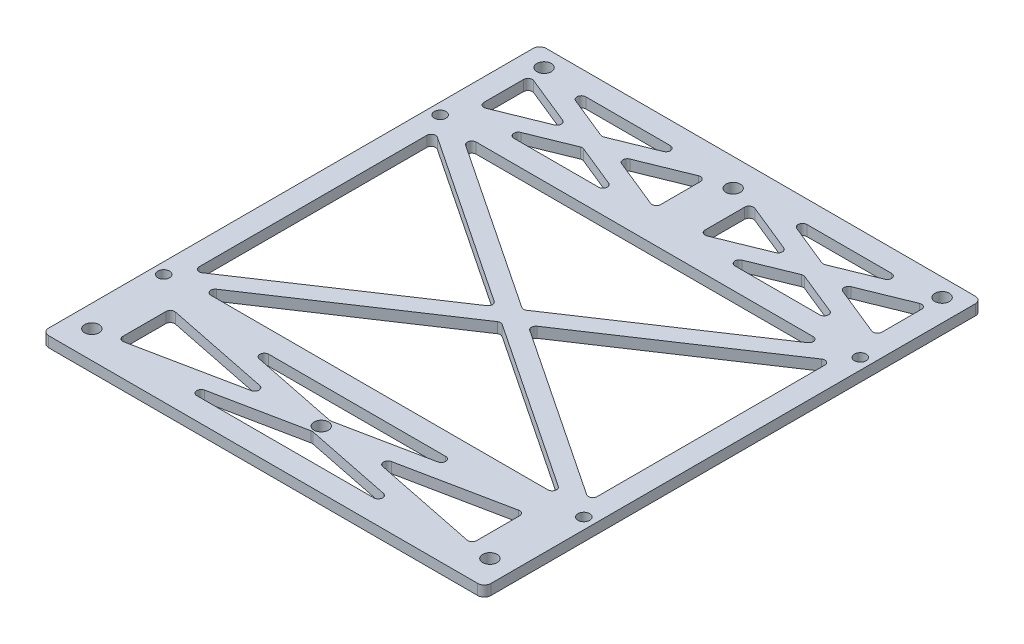
SolidWorks part; units mm, degrees
ref_plane "Front Plane" through (0, 0, 0) normal (0, 0, 1) x (1, 0, 0)
ref_plane "Top Plane" through (0, 0, 0) normal (0, 1, 0) x (1, 0, 0)
ref_plane "Right Plane" through (0, 0, 0) normal (1, 0, 0) x (0, 0, -1)
sketch "Sketch2" plane through (0, 0, 0) normal (0, 1, 0) x (1, 0, 0)
  line L0 (-90, -100) -> (90, -100) construction
  line L1 (-100, -112.5) -> (100, -112.5)
  line L2 (-100, -112.5) -> (-100, 112.5)
  line L3 (-100, 112.5) -> (100, 112.5)
  line L4 (100, -112.5) -> (100, 112.5)
  line L5 (-100, -112.5) -> (100, 112.5) construction
  line L6 (-100, 112.5) -> (100, -112.5) construction
  line L7 (-90, 100) -> (90, 100) construction
  line L8 (-95, -62.5) -> (95, -62.5) construction
  line L9 (-95, -62.5) -> (-95, 62.5) construction
  line L10 (-95, 62.5) -> (95, 62.5) construction
  line L11 (95, -62.5) -> (95, 62.5) construction
  line L12 (-95, -62.5) -> (95, 62.5) construction
  line L13 (-95, 62.5) -> (95, -62.5) construction
  circle A0 centre (-90, -100) radius 76.2 construction
  circle A1 centre (90, -100) radius 76.2 construction
  circle A2 centre (0, 100) radius 76.2 construction
  point P0 (0, 0)
  point P15 (0, 0)
  point P16 (0, -100)
  point P21 (0, 100)
  dimension "D3" = 152.4
  dimension "D1" = 200
  dimension "D2" = 225
  dimension "D4" = 100
  dimension "D5" = 180
  dimension "D6" = 100
  dimension "D7" = 190
  dimension "D8" = 125
extrude "Boss-Extrude1" add sketch "Sketch2" along normal blind 4.7625
hole_wizard "M5 Clearance Hole1" positions "Sketch5" profile "Sketch6" hole size "M5" standard "ANSI Metric" end condition through all
sketch "Sketch5" plane through (0, 4.7625, 0) normal (0, 1, 0) x (1, 0, 0)
  point P0 (-95, 62.5)
  point P3 (-95, -62.5)
  point P6 (95, -62.5)
  point P9 (95, 62.5)
sketch "Sketch6" plane through (-95, 4.7625, -62.5) normal (1, 0, 0) x (0, 0, 1)
  line L0 (0, 0) -> (0, 4.7625)
  line L1 (0, 4.7625) -> (2.65, 4.7625)
  line L2 (2.65, 4.7625) -> (2.65, 0)
  line L5 (2.65, 0) -> (0, 0)
  line L11 (0, -6.35) -> (0, 107.95) construction
  dimension "Thru Hole Dia." = 5.3
  dimension "Thru Hole Depth" = 4.7625
hole_wizard "1/4 Clearance Hole1" positions "Sketch3" profile "Sketch4" hole size "1/4" standard "ANSI Inch" end condition through all
sketch "Sketch3" plane through (0, 4.7625, 0) normal (0, 1, 0) x (1, 0, 0)
  point P0 (0, 100)
  point P3 (-90, -100)
  point P6 (90, -100)
sketch "Sketch4" plane through (0, 4.7625, -100) normal (1, 0, 0) x (0, 0, 1)
  line L0 (0, 0) -> (0, 4.7625)
  line L1 (0, 4.7625) -> (3.2639, 4.7625)
  line L2 (3.2639, 4.7625) -> (3.2639, 0)
  line L5 (3.2639, 0) -> (0, 0)
  line L11 (0, -6.35) -> (0, 107.95) construction
  dimension "Thru Hole Dia." = 6.5278
  dimension "Thru Hole Depth" = 4.7625
sketch "Sketch7" plane through (0, 4.7625, 0) normal (0, 1, 0) x (1, 0, 0)
  line L0 (-92.2188, 56.6718) -> (87.7812, -63.3282) construction
  line L1 (-90, -60) -> (90, -60) construction
  line L2 (-90, -60) -> (-90, 60) construction
  line L3 (-90, 60) -> (90, 60) construction
  line L4 (90, -60) -> (90, 60) construction
  line L5 (-90, -60) -> (90, 60) construction
  line L6 (-90, 60) -> (90, -60) construction
  line L7 (-87.7812, -63.3282) -> (92.2188, 56.6718) construction
  line L8 (-87.7812, 63.3282) -> (92.2188, -56.6718) construction
  line L9 (-92.2188, -56.6718) -> (87.7812, 63.3282) construction
  line L10 (-82.7889, 60) -> (82.7889, 60)
  line L11 (82.7889, 60) -> (0, 4.8074)
  line L12 (0, 4.8074) -> (-82.7889, 60)
  line L13 (-90, 55.1926) -> (-7.2111, 0)
  line L14 (-7.2111, 0) -> (-90, -55.1926)
  line L15 (-90, -55.1926) -> (-90, 55.1926)
  line L16 (90, 55.1926) -> (7.2111, 0)
  line L17 (7.2111, 0) -> (90, -55.1926)
  line L18 (90, -55.1926) -> (90, 55.1926)
  line L19 (-82.7889, -60) -> (0, -4.8074)
  line L20 (0, -4.8074) -> (82.7889, -60)
  line L21 (82.7889, -60) -> (-82.7889, -60)
  line L22 (-100, -112.5) -> (100, -112.5) construction
  line L23 (-80, -102.5) -> (80, -102.5) construction
  line L24 (-80, -102.5) -> (-80, -70) construction
  line L25 (-80, -70) -> (80, -70) construction
  line L26 (80, -102.5) -> (80, -70) construction
  line L27 (-80, -102.5) -> (80, -70) construction
  line L28 (-80, -70) -> (80, -102.5) construction
  line L29 (-80.7962, -73.9199) -> (79.2038, -106.4199) construction
  line L30 (-79.2038, -106.4199) -> (80.7962, -73.9199) construction
  line L31 (-79.2038, -66.0801) -> (80.7962, -98.5801) construction
  line L32 (-80.7962, -98.5801) -> (79.2038, -66.0801) construction
  line L33 (-80, -74.0817) -> (-20.0945, -86.25)
  line L34 (-20.0945, -86.25) -> (-80, -98.4183)
  line L35 (-80, -98.4183) -> (-80, -74.0817)
  line L36 (-59.9055, -70) -> (59.9055, -70)
  line L37 (59.9055, -70) -> (0, -82.1683)
  line L38 (0, -82.1683) -> (-59.9055, -70)
  line L39 (80, -74.0817) -> (20.0945, -86.25)
  line L40 (20.0945, -86.25) -> (80, -98.4183)
  line L41 (80, -98.4183) -> (80, -74.0817)
  line L42 (-59.9055, -102.5) -> (0, -90.3317)
  line L43 (0, -90.3317) -> (59.9055, -102.5)
  line L44 (59.9055, -102.5) -> (-59.9055, -102.5)
  line L45 (-50, 86.25) -> (50, 86.25) construction
  line L46 (-90, 70) -> (-10, 70) construction
  line L47 (-90, 70) -> (-90, 102.5) construction
  line L48 (-90, 102.5) -> (-10, 102.5) construction
  line L49 (-10, 70) -> (-10, 102.5) construction
  line L50 (-90, 70) -> (-10, 102.5) construction
  line L51 (-90, 102.5) -> (-10, 70) construction
  line L52 (10, 70) -> (90, 70) construction
  line L53 (10, 70) -> (10, 102.5) construction
  line L54 (10, 102.5) -> (90, 102.5) construction
  line L55 (90, 70) -> (90, 102.5) construction
  line L56 (10, 70) -> (90, 102.5) construction
  line L57 (10, 102.5) -> (90, 70) construction
  line L58 (100, 112.5) -> (-100, 112.5) construction
  line L59 (-91.5055, 98.7941) -> (-11.5055, 66.2941) construction
  line L60 (-88.4945, 66.2941) -> (-8.4945, 98.7941) construction
  line L61 (8.4945, 98.7941) -> (88.4945, 66.2941) construction
  line L62 (11.5055, 66.2941) -> (91.5055, 98.7941) construction
  line L63 (-88.4945, 106.2059) -> (-8.4945, 73.7059) construction
  line L64 (-91.5055, 73.7059) -> (-11.5055, 106.2059) construction
  line L65 (11.5055, 106.2059) -> (91.5055, 73.7059) construction
  line L66 (8.4945, 73.7059) -> (88.4945, 106.2059) construction
  line L67 (90, 98.1825) -> (60.6276, 86.25)
  line L68 (60.6276, 86.25) -> (90, 74.3175)
  line L69 (90, 74.3175) -> (90, 98.1825)
  line L70 (79.3724, 102.5) -> (50, 90.5675)
  line L71 (50, 90.5675) -> (20.6276, 102.5)
  line L72 (20.6276, 102.5) -> (79.3724, 102.5)
  line L73 (10, 98.1825) -> (39.3724, 86.25)
  line L74 (39.3724, 86.25) -> (10, 74.3175)
  line L75 (10, 74.3175) -> (10, 98.1825)
  line L76 (20.6276, 70) -> (50, 81.9325)
  line L77 (50, 81.9325) -> (79.3724, 70)
  line L78 (79.3724, 70) -> (20.6276, 70)
  line L79 (-79.3724, 102.5) -> (-20.6276, 102.5)
  line L80 (-20.6276, 102.5) -> (-50, 90.5675)
  line L81 (-50, 90.5675) -> (-79.3724, 102.5)
  line L82 (-10, 98.1825) -> (-39.3724, 86.25)
  line L83 (-39.3724, 86.25) -> (-10, 74.3175)
  line L84 (-10, 74.3175) -> (-10, 98.1825)
  line L85 (-50, 81.9325) -> (-79.3724, 70)
  line L86 (-79.3724, 70) -> (-20.6276, 70)
  line L87 (-20.6276, 70) -> (-50, 81.9325)
  line L88 (-90, 74.3175) -> (-60.6276, 86.25)
  line L89 (-60.6276, 86.25) -> (-90, 98.1825)
  line L90 (-90, 98.1825) -> (-90, 74.3175)
  point P0 (0, 0)
  point P28 (0, -86.25)
  point P55 (-50, 86.25)
  point P61 (50, 86.25)
  point P68 (0, 86.25)
  dimension "D3" = 120
  dimension "D4" = 180
  dimension "D5" = 10
  dimension "D6" = 10
  dimension "D7" = 160
  dimension "D10" = 10
  dimension "D11" = 10
  dimension "D12" = 20
  dimension "D1" = 4
  dimension "D2" = 4
  dimension "D8" = 4
  dimension "D9" = 4
  dimension "D13" = 4
  dimension "D14" = 4
extrude "Cut-Extrude1" cut sketch "Sketch7" against normal through all
sketch "Sketch10" plane through (0, 4.7625, 0) normal (0, 1, 0) x (1, 0, 0)
  line L0 (-90, 104.5) -> (90, 104.5) construction
  line L3 (-100, 112.5) -> (100, 112.5) construction
  point P5 (0, 100)
  point P6 (0, 104.5)
  dimension "D1" = 8
  dimension "D2" = 180
hole_wizard "1/4 Clearance Hole2" positions "Sketch8" profile "Sketch9" hole size "1/4" standard "ANSI Inch" end condition through all
sketch "Sketch8" plane through (0, 4.7625, 0) normal (0, 1, 0) x (1, 0, 0)
  point P0 (0, -86.25)
  point P3 (-90, 104.5)
  point P6 (90, 104.5)
sketch "Sketch9" plane through (0, 4.7625, 86.25) normal (1, 0, 0) x (0, 0, 1)
  line L0 (0, 0) -> (0, 4.7625)
  line L1 (0, 4.7625) -> (3.2639, 4.7625)
  line L2 (3.2639, 4.7625) -> (3.2639, 0)
  line L5 (3.2639, 0) -> (0, 0)
  line L11 (0, -6.35) -> (0, 107.95) construction
  dimension "Thru Hole Dia." = 6.5278
  dimension "Thru Hole Depth" = 4.7625
fillet "Fillet1" radius 2 48 edges at (-82.7889, 2.3813, -60) (82.7889, 2.3813, -60) (0, 2.3813, -4.8074) (-79.3724, 2.3813, -102.5) (-20.6276, 2.3813, -102.5) (-50, 2.3813, -90.5675) (20.6276, 2.3813, -70) (50, 2.3813, -81.9325) (79.3724, 2.3813, -70) (10, 2.3813, -98.1825) (39.3724, 2.3813, -86.25) (10, 2.3813, -74.3175) (79.3724, 2.3813, -102.5) (50, 2.3813, -90.5675) (20.6276, 2.3813, -102.5) (-90, 2.3813, -98.1825) (-60.6276, 2.3813, -86.25) (-90, 2.3813, -74.3175) (-10, 2.3813, -74.3175) (-39.3724, 2.3813, -86.25) (-10, 2.3813, -98.1825) (-20.6276, 2.3813, -70) (-79.3724, 2.3813, -70) (-50, 2.3813, -81.9325) (-59.9055, 2.3813, 70) (59.9055, 2.3813, 70) (0, 2.3813, 82.1683) (0, 2.3813, 4.8074) (82.7889, 2.3813, 60) (90, 2.3813, 55.1926) (7.2111, 2.3813, 0) (90, 2.3813, -55.1926) (-90, 2.3813, -55.1926) (-7.2111, 2.3813, 0) (90, 2.3813, -74.3175) (60.6276, 2.3813, -86.25) (90, 2.3813, -98.1825) (-59.9055, 2.3813, 102.5) (0, 2.3813, 90.3317) (59.9055, 2.3813, 102.5) (80, 2.3813, 98.4183) (20.0945, 2.3813, 86.25) (80, 2.3813, 74.0817) (-80, 2.3813, 74.0817) (-20.0945, 2.3813, 86.25) (-80, 2.3813, 98.4183) (-82.7889, 2.3813, 60) (-90, 2.3813, 55.1926)
fillet "Fillet2" radius 3 4 edges at (100, 2.3813, 112.5) (-100, 2.3813, 112.5) (100, 2.3813, -112.5) (-100, 2.3813, -112.5)
